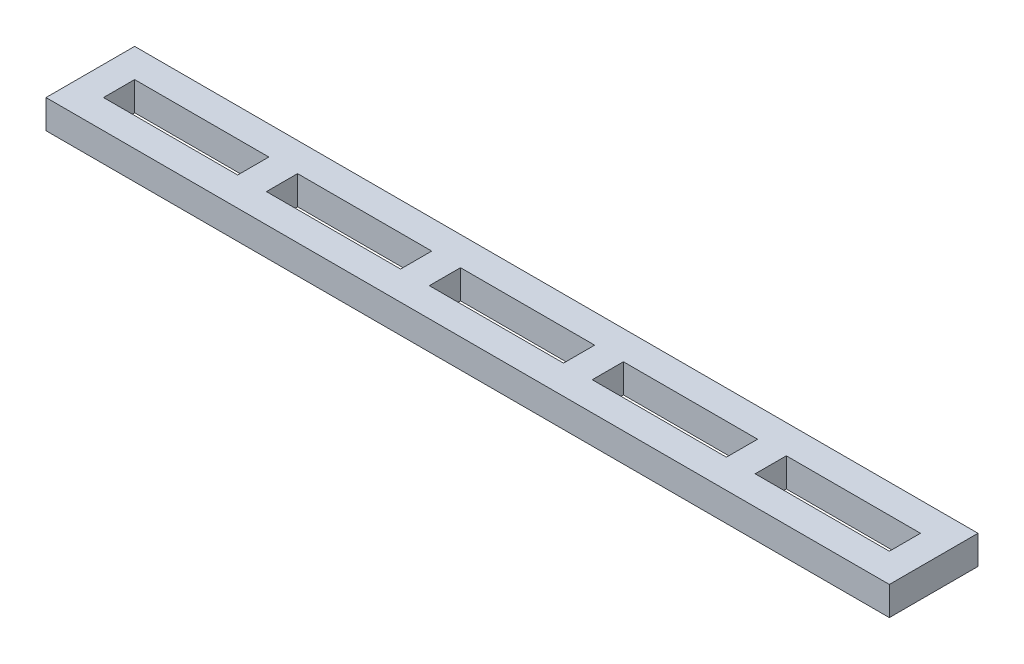
SolidWorks part; units mm, degrees
material "Pine"
ref_plane "Front Plane" through (0, 0, 0) normal (0, 0, 1) x (1, 0, 0)
ref_plane "Top Plane" through (0, 0, 0) normal (0, 1, 0) x (1, 0, 0)
ref_plane "Right Plane" through (0, 0, 0) normal (1, 0, 0) x (0, 0, -1)
sketch "Sketch1" plane through (0, 0, 0) normal (1, 0, 0) x (0, 0, -1)
  line L1 (-29.3688, -9.525) -> (29.3687, -9.525)
  line L2 (-29.3688, -9.525) -> (-29.3688, 9.525)
  line L3 (-29.3688, 9.525) -> (29.3687, 9.525)
  line L4 (29.3687, -9.525) -> (29.3687, 9.525)
  line L5 (-29.3688, -9.525) -> (29.3687, 9.525) construction
  line L6 (-29.3688, 9.525) -> (29.3687, -9.525) construction
  point P0 (0, 0)
  dimension "D1" = 58.7375
  dimension "D2" = 19.05
extrude "Boss-Extrude1" add sketch "Sketch1" along normal mid plane 558.8
sketch "Sketch2" plane through (0, 9.525, 0) normal (0, 1, 0) x (1, 0, 0)
  line L10 (171.45, 0) -> (152.4, 0) construction
  line L11 (-260.35, 10.3187) -> (-171.45, 10.3187)
  line L12 (-260.35, 10.3187) -> (-260.35, -10.3187)
  line L13 (-260.35, -10.3187) -> (-171.45, -10.3187)
  line L14 (260.35, 10.3187) -> (260.35, -10.3187)
  line L15 (260.35, 0) -> (279.4, 0) construction
  line L16 (279.4, 29.3687) -> (279.4, -29.3688) construction
  line L17 (-260.35, 0) -> (-279.4, 0) construction
  line L18 (-279.4, 29.3687) -> (-279.4, -29.3688) construction
  line L19 (215.9, 10.3187) -> (215.9, 29.3687) construction
  line L20 (279.4, 29.3687) -> (-279.4, 29.3687) construction
  line L22 (-171.45, 10.3187) -> (-171.45, -10.3187)
  line L23 (-152.4, 10.3187) -> (-63.5, 10.3187)
  line L24 (-152.4, 10.3187) -> (-152.4, -10.3187)
  line L25 (-152.4, -10.3187) -> (-63.5, -10.3187)
  line L26 (-63.5, 10.3187) -> (-63.5, -10.3187)
  line L27 (-44.45, 10.3187) -> (44.45, 10.3187)
  line L28 (-44.45, 10.3187) -> (-44.45, -10.3187)
  line L29 (-44.45, -10.3187) -> (44.45, -10.3187)
  line L30 (44.45, 10.3187) -> (44.45, -10.3187)
  line L31 (63.5, 10.3187) -> (152.4, 10.3187)
  line L32 (63.5, 10.3187) -> (63.5, -10.3187)
  line L33 (63.5, -10.3187) -> (152.4, -10.3187)
  line L34 (152.4, 10.3187) -> (152.4, -10.3187)
  line L35 (260.35, 10.3187) -> (171.45, 10.3187)
  line L37 (260.35, -10.3187) -> (171.45, -10.3187)
  line L38 (171.45, 10.3187) -> (171.45, -10.3187)
  line L40 (63.5, 0) -> (44.45, 0) construction
  line L42 (-44.45, 0) -> (-63.5, 0) construction
  line L44 (-152.4, 0) -> (-171.45, 0) construction
  dimension "D2" = 19.05
extrude "Cut-Extrude1" cut sketch "Sketch2" against normal through all
